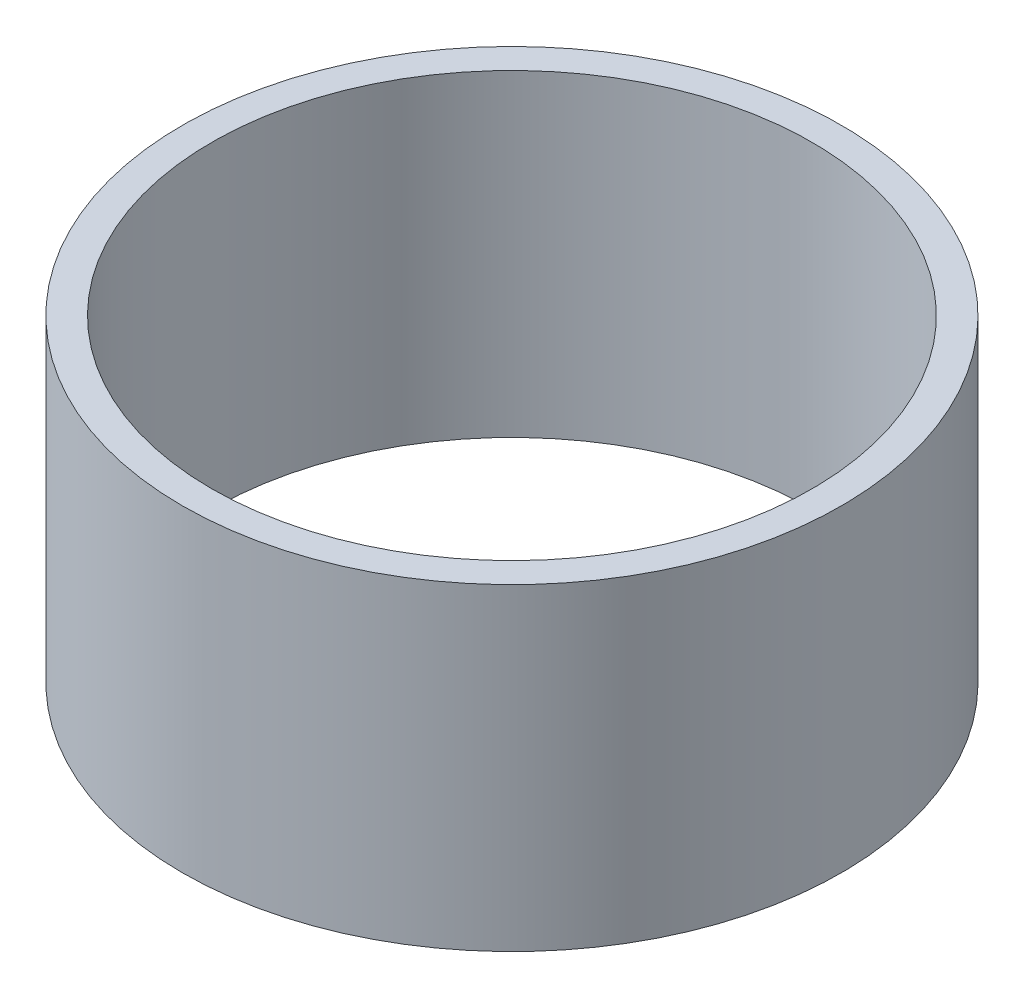
SolidWorks part; units mm, degrees
material "6061 合金"
ref_plane "前视基准面" through (0, 0, 0) normal (0, 0, 1) x (1, 0, 0)
ref_plane "上视基准面" through (0, 0, 0) normal (0, 1, 0) x (1, 0, 0)
ref_plane "右视基准面" through (0, 0, 0) normal (1, 0, 0) x (0, 0, -1)
sketch "草图1" plane through (0, 0, 0) normal (0, 1, 0) x (1, 0, 0)
  circle A0 centre (0, 0) radius 14
  circle A1 centre (0, 0) radius 12.75
  dimension "D1" = 25.5
  dimension "D2" = 28
extrude "凸台-拉伸1" add sketch "草图1" along normal blind 13.5
